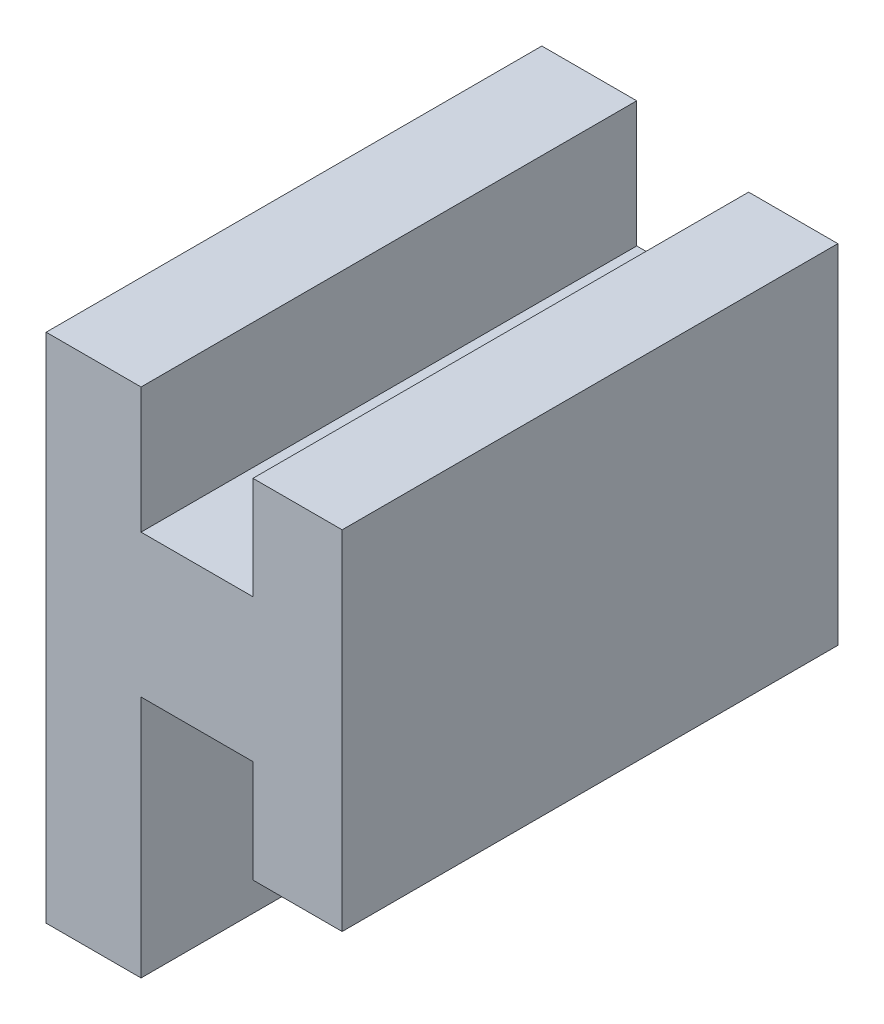
SolidWorks part; units mm, degrees
ref_plane "Front Plane" through (0, 0, 0) normal (0, 0, 1) x (1, 0, 0)
ref_plane "Top Plane" through (0, 0, 0) normal (0, 1, 0) x (1, 0, 0)
ref_plane "Right Plane" through (0, 0, 0) normal (1, 0, 0) x (0, 0, -1)
sketch "Sketch2" plane through (0, 0, 0) normal (0, 0, 1) x (1, 0, 0)
  line L0 (-32, -20.059) -> (-34.1144, -20.059) construction
  line L1 (-34.1144, -20.059) -> (-34.1144, -9.533) construction
  line L2 (-34.1144, -9.533) -> (-32, -9.533) construction
  line L3 (-32, -8.1732) -> (-32, -12.0692) construction
  line L4 (-32, -9.533) -> (-32, -12.0692) construction
  line L5 (-32, -12.0692) -> (-29.9428, -12.0692) construction
  line L6 (-29.9428, -12.0692) -> (-29.9428, -10) construction
  line L7 (-29.9428, -12.0692) -> (-29.9428, -10) construction
  line L8 (-29.9428, -10) -> (-27.9428, -10) construction
  line L9 (-27.9428, -10) -> (-27.9428, -17.2189) construction
  line L10 (-27.9428, -17.2189) -> (-29.9428, -17.2189) construction
  line L11 (-29.9428, -17.2189) -> (-29.9428, -15.1497) construction
  line L12 (-29.9428, -15.1497) -> (-32, -15.1497) construction
  line L13 (-32, -15.1497) -> (-32, -20.059) construction
  line L14 (-29.9428, -15.1497) -> (-32, -15.1497) construction
  line L15 (-32, -15.1497) -> (-32, -20.059) construction
  line L16 (-32.1, -9.633) -> (-32.1, -12.1692)
  line L17 (-32.1, -12.1692) -> (-29.8428, -12.1692)
  line L18 (-29.8428, -12.1692) -> (-29.8428, -10.1)
  line L19 (-29.8428, -10.1) -> (-28.0428, -10.1)
  line L20 (-28.0428, -10.1) -> (-28.0428, -17.1189)
  line L21 (-28.0428, -17.1189) -> (-29.8428, -17.1189)
  line L22 (-29.8428, -17.1189) -> (-29.8428, -15.0497)
  line L23 (-29.8428, -15.0497) -> (-32.1, -15.0497)
  line L24 (-32.1, -15.0497) -> (-32.1, -19.959)
  line L25 (-32.1, -19.959) -> (-34.0144, -19.959)
  line L26 (-34.0144, -19.959) -> (-34.0144, -9.633)
  line L27 (-34.0144, -9.633) -> (-32.1, -9.633)
  dimension "D1" = 0.1
extrude "Boss-Extrude1" add sketch "Sketch2" against normal blind 10
